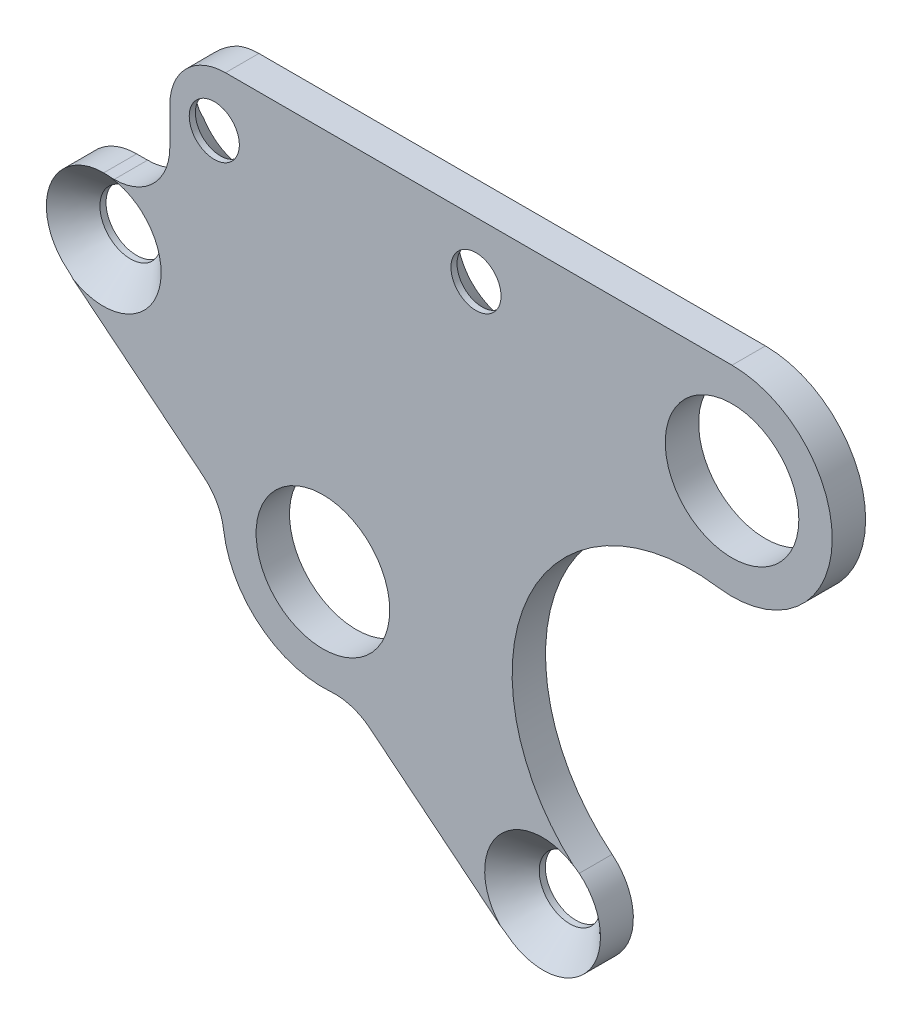
SolidWorks part; units mm, degrees
material "6061-T6 (SS)"
ref_plane "Front Plane" through (0, 0, 0) normal (0, 0, 1) x (1, 0, 0)
ref_plane "Top Plane" through (0, 0, 0) normal (0, 1, 0) x (1, 0, 0)
ref_plane "Right Plane" through (0, 0, 0) normal (1, 0, 0) x (0, 0, -1)
sketch "Sketch1" plane through (0, 0, 0) normal (0, 0, 1) x (1, 0, 0)
  line L0 (-19.7311, 15.9951) -> (19.7311, -15.9951) construction
  line L1 (0, 0) -> (33.7047, 7.1273) construction
  line L2 (-19.7311, 15.9951) -> (19.7311, -15.9951) construction
  line L3 (-16.4849, 19.9996) -> (22.9774, -11.9906) construction
  line L4 (-22.9774, 11.9906) -> (16.4849, -19.9996) construction
  line L5 (0, -25.4) -> (-50000, -25.4) construction
  line L6 (0, 0) -> (0, 34.45) construction
  line L7 (16.4849, -19.9996) -> (2.4846, -8.6502)
  line L8 (-22.9774, 11.9906) -> (-8.9771, 0.6413)
  line L9 (-14.0654, 21.1501) -> (-13.75, 21.1501)
  line L10 (-13.75, 34.45) -> (13.75, 34.45)
  line L11 (-13.75, 34.45) -> (-13.75, 21.1501)
  line L12 (-13.75, 0) -> (13.75, 0) construction
  line L13 (13.75, 34.45) -> (13.75, 0) construction
  line L14 (-13.75, 34.45) -> (13.75, 0) construction
  line L15 (-13.75, 0) -> (13.75, 34.45) construction
  line L16 (-13.75, 21.5558) -> (-13.75, 34.45) construction
  line L17 (-13.75, 34.45) -> (13.75, 34.45) construction
  line L18 (13.75, 34.45) -> (36.75, 34.45)
  line L20 (-19.7311, 21.1501) -> (-14.0654, 21.1501)
  line L23 (-13.75, 21.1501) -> (-13.75, 21.3564) construction
  line L24 (-13.75, 21.3564) -> (-13.75, 21.5558) construction
  line L25 (-13.75, 21.1501) -> (-13.75, 17.7825) construction
  line L26 (-13.75, 11.1465) -> (-13.75, 7.2622) construction
  line L27 (-13.75, 17.7825) -> (-13.75, 11.1465) construction
  line L28 (-13.75, 4.5104) -> (-13.75, 0) construction
  line L29 (-13.75, 7.2622) -> (-13.75, 4.5104) construction
  circle A0 centre (0, 0) radius 25.4 construction
  circle A1 centre (0, 0) radius 15.55 construction
  arc A2 (-16.4849, 19.9996) -> (-22.9774, 11.9906) centre (-19.7311, 15.9951) ccw construction
  arc A3 (16.4849, -19.9996) -> (22.9774, -11.9906) centre (19.7311, -15.9951) ccw construction
  circle A4 centre (-19.7311, 15.9951) radius 2
  circle A5 centre (19.7311, -15.9951) radius 2
  circle A6 centre (0, 0) radius 6
  arc A7 (-8.9771, 0.6413) -> (2.4846, -8.6502) centre (0, 0) ccw
  arc A8 (-22.9774, 11.9906) -> (-19.7311, 21.1501) centre (-19.7311, 15.9951) cw
  circle A9 centre (36.75, 25.45) radius 6
  arc A11 (22.9774, -11.9906) -> (16.4849, -19.9996) centre (19.7311, -15.9951) cw
  arc A14 (-6.9913, 5.6675) -> (-8.9771, 0.6413) centre (0, 0) ccw construction
  circle A15 centre (0, 0) radius 9 construction
  arc A16 (-2.4846, 8.6502) -> (-6.9913, 5.6675) centre (0, 0) ccw construction
  arc A17 (8.8053, 1.862) -> (0, 9) centre (0, 0) ccw construction
  arc A18 (0, 9) -> (-2.4846, 8.6502) centre (0, 0) ccw construction
  arc A19 (9, 0) -> (8.8053, 1.862) centre (0, 0) ccw construction
  arc A20 (8.9771, -0.6413) -> (9, 0) centre (0, 0) ccw construction
  arc A21 (6.9913, -5.6675) -> (8.9771, -0.6413) centre (0, 0) ccw construction
  arc A22 (2.4846, -8.6502) -> (6.9913, -5.6675) centre (0, 0) ccw construction
  arc A25 (36.75, 34.45) -> (35.4615, 16.5427) centre (36.75, 25.45) cw
  arc A26 (22.9774, -11.9906) -> (35.4615, 16.5427) centre (33.1489, 0.5568) cw
  point P6 (0, 0)
  point P8 (0, 0)
  point P29 (0, 17.225)
  dimension "D1" = 50.8
  dimension "D4" = 31.1
  dimension "D5" = 50
  dimension "D7" = 4
  dimension "D9" = 12
  dimension "D12" = 3
  dimension "D13" = 12
  dimension "D2" = 50.8
  dimension "D3" = 50.97
  dimension "D6" = 10.31
  dimension "D8" = 50.97
  dimension "D11" = 27.5
  dimension "D14" = 17
  dimension "D10" = 3
extrude "Boss-Extrude1" add sketch "Sketch1" along normal blind 3
fillet "Fillet1" radius 5 4 edges at (-8.9771, 0.6413, 1.5) (2.4846, -8.6502, 1.5) (-13.75, 21.1501, 1.5) (-13.75, 34.45, 1.5)
hole_wizard "CSK for M4 Countersunk Flat Head Screw1" positions "Sketch2" profile "Sketch3" countersink size "M4" standard "ISO" end condition through all
sketch "Sketch2" plane through (0, 0, 0) normal (0, 0, 1) x (1, 0, 0)
  line L0 (13.75, 34.45) -> (13.75, 0) construction
  line L1 (-13.75, 34.45) -> (13.75, 0) construction
  line L2 (-13.75, 34.45) -> (13.75, 34.45) construction
  line L3 (13.75, 34.45) -> (36.75, 34.45) construction
  point P0 (13.75, 29.45)
  point P4 (-9.7587, 29.45)
  point P12 (13.75, 28.2863)
  dimension "D1" = 5
  dimension "D2" = 5
sketch "Sketch3" plane through (13.75, 29.45, 0) normal (1, 0, 0) x (0, 1, 0)
  line L0 (0, 0) -> (0, 3)
  line L1 (0, 3) -> (2.25, 3)
  line L2 (2.25, 3) -> (2.25, 2.45)
  line L3 (2.25, 2.45) -> (4.7, 0)
  line L5 (4.7, 0) -> (0, 0)
  line L6 (-2.25, 2.45) -> (-4.7, 0) construction
  line L11 (0, -6.35) -> (0, 107.95) construction
  dimension "Thru Hole Dia." = 4.5
  dimension "Thru Hole Depth" = 3
  dimension "Near C'Sink Dia." = 9.4
  dimension "Near C'Sink Angle" = 90
hole_wizard "CSK for M5 Countersunk Flat Head Screw1" positions "Sketch5" profile "Sketch6" countersink size "M5" standard "ISO" end condition through all
sketch "Sketch5" plane through (0, 0, 3) normal (0, 0, -1) x (-1, 0, 0)
  point P0 (19.7311, 15.9951)
  point P3 (-19.7311, -15.9951)
sketch "Sketch6" plane through (-19.7311, 15.9951, 3) normal (1, 0, 0) x (0, -1, 0)
  line L0 (0, 0) -> (0, 3)
  line L1 (0, 3) -> (2.75, 3)
  line L2 (2.75, 3) -> (2.75, 2.45)
  line L3 (2.75, 2.45) -> (5.2, 0)
  line L5 (5.2, 0) -> (0, 0)
  line L6 (-2.75, 2.45) -> (-5.2, 0) construction
  line L11 (0, -6.35) -> (0, 107.95) construction
  dimension "Thru Hole Dia." = 5.5
  dimension "Thru Hole Depth" = 3
  dimension "Near C'Sink Dia." = 10.4
  dimension "Near C'Sink Angle" = 90
